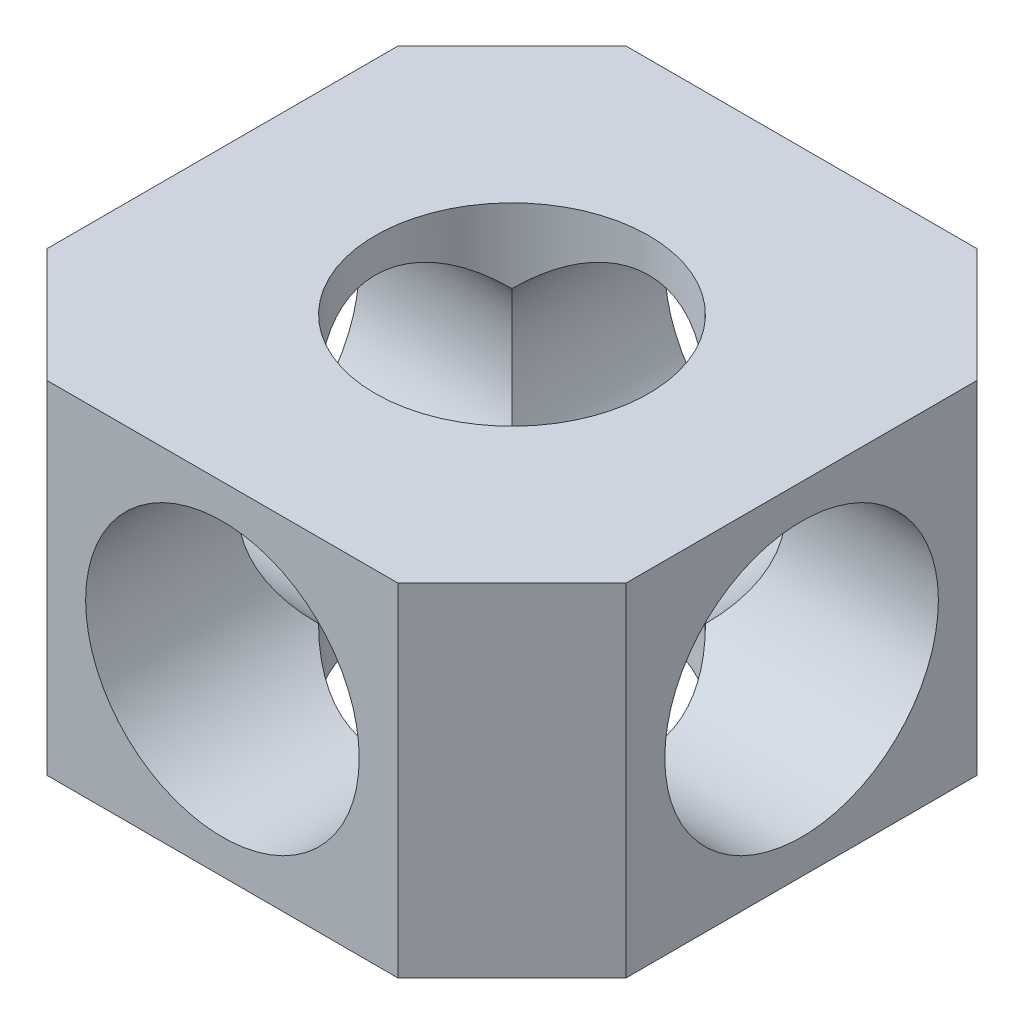
SolidWorks part; units mm, degrees
ref_plane "Front Plane" through (0, 0, 0) normal (0, 0, 1) x (1, 0, 0)
ref_plane "Top Plane" through (0, 0, 0) normal (0, 1, 0) x (1, 0, 0)
ref_plane "Right Plane" through (0, 0, 0) normal (1, 0, 0) x (0, 0, -1)
sketch "Sketch1" plane through (0, 0, 0) normal (0, 1, 0) x (1, 0, 0)
  line L1 (-12.7, 12.7) -> (12.7, 12.7)
  line L2 (-12.7, 12.7) -> (-12.7, -12.7)
  line L3 (-12.7, -12.7) -> (12.7, -12.7)
  line L4 (12.7, 12.7) -> (12.7, -12.7)
  line L5 (-12.7, 12.7) -> (12.7, -12.7) construction
  line L6 (-12.7, -12.7) -> (12.7, 12.7) construction
  point P0 (0, 0)
  dimension "D1" = 25.4
  dimension "D2" = 25.4
extrude "Boss-Extrude1" add sketch "Sketch1" along normal mid plane 15
chamfer "Chamfer1" distance 5 angle 45 4 edges at (-12.7, 0, 12.7) (-12.7, 0, -12.7) (12.7, 0, -12.7) (12.7, 0, 12.7)
hole_wizard "Hole1" positions "Sketch2" profile "Sketch3" legacy
sketch "Sketch2" plane through (0, 7.5, 0) normal (0, 1, 0) x (1, 0, 0)
  point P0 (0, 0)
sketch "Sketch3" plane through (0, 7.5, 0) normal (1, 0, 0) x (0, 0, 1)
  line L0 (0, 0) -> (0, 100)
  line L1 (0, 100) -> (6, 100)
  line L2 (6, 100) -> (6, 0)
  line L3 (6, 0) -> (0, 0)
  line L4 (0, 110) -> (0, -10) construction
  dimension "Diameter" = 12
  dimension "Depth" = 100
hole_wizard "Hole2" positions "Sketch4" profile "Sketch5" legacy
sketch "Sketch4" plane through (-12.7, 0, 0) normal (-1, 0, 0) x (0, 0, 1)
  point P0 (0, 0)
sketch "Sketch5" plane through (-12.7, 0, 0) normal (0, 1, 0) x (0, 0, 1)
  line L0 (0, 0) -> (0, 100)
  line L1 (0, 100) -> (6, 100)
  line L2 (6, 100) -> (6, 0)
  line L3 (6, 0) -> (0, 0)
  line L4 (0, 110) -> (0, -10) construction
  dimension "Diameter" = 12
  dimension "Depth" = 100
hole_wizard "Hole3" positions "Sketch6" profile "Sketch7" legacy
sketch "Sketch6" plane through (0, 0, 12.7) normal (0, 0, 1) x (1, 0, 0)
  point P0 (0, 0)
sketch "Sketch7" plane through (0, 0, 12.7) normal (1, 0, 0) x (0, -1, 0)
  line L0 (0, 0) -> (0, 100)
  line L1 (0, 100) -> (6, 100)
  line L2 (6, 100) -> (6, 0)
  line L3 (6, 0) -> (0, 0)
  line L4 (0, 110) -> (0, -10) construction
  dimension "Diameter" = 12
  dimension "Depth" = 100
